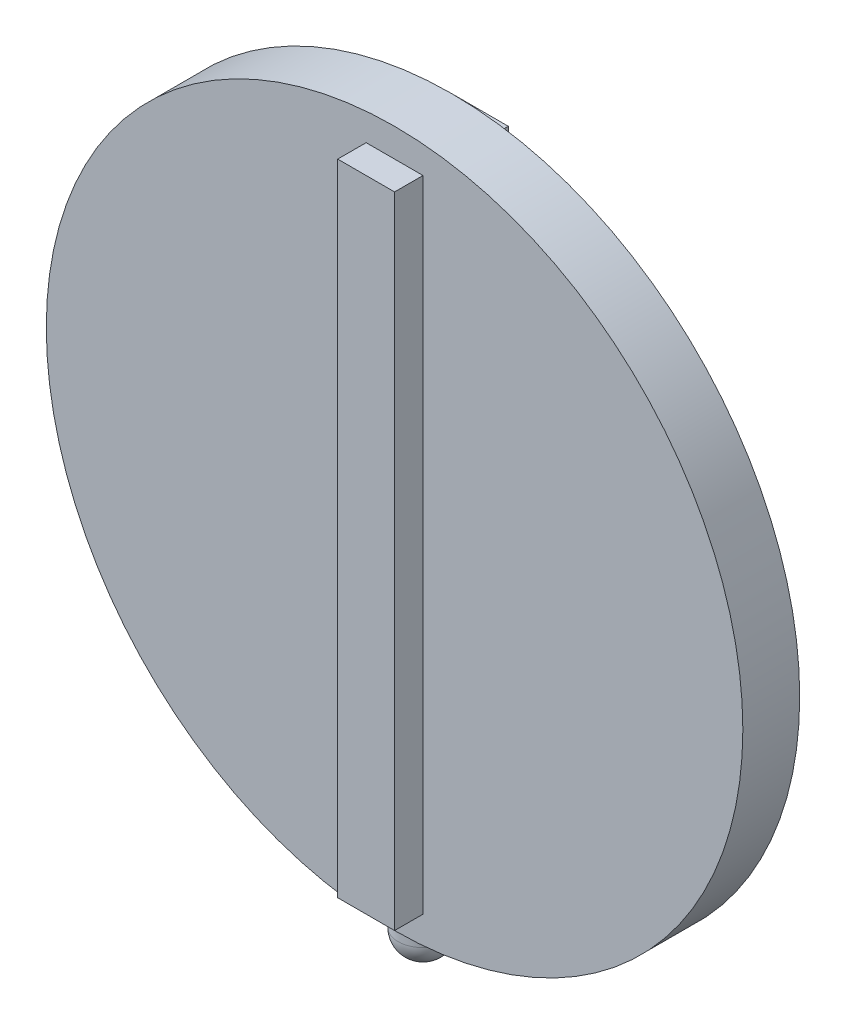
SolidWorks part; units mm, degrees
ref_plane "前视基准面" through (0, 0, 0) normal (0, 0, 1) x (1, 0, 0)
ref_plane "上视基准面" through (0, 0, 0) normal (0, 1, 0) x (1, 0, 0)
ref_plane "右视基准面" through (0, 0, 0) normal (1, 0, 0) x (0, 0, -1)
other "Configuration Table"
sketch "草图1" plane through (0, 0, 0) normal (0, 0, 1) x (1, 0, 0)
  circle A0 centre (0, 0) radius 24.5
  dimension "D1" = 49
extrude "凸台-拉伸1" add sketch "草图1" along normal blind 4
sketch "草图2" plane through (0, 0, 4) normal (0, 0, 1) x (1, 0, 0)
  line L1 (-2, 22.5) -> (2, 22.5)
  line L2 (-2, 22.5) -> (-2, -22.5)
  line L3 (-2, -22.5) -> (2, -22.5)
  line L4 (2, 22.5) -> (2, -22.5)
  line L5 (-2, 22.5) -> (2, -22.5) construction
  line L6 (-2, -22.5) -> (2, 22.5) construction
  point P0 (0, 0)
  dimension "D1" = 45
  dimension "D2" = 4
extrude "凸台-拉伸2" add sketch "草图2" along normal blind 2 contours L2 L1 L4 L3
ref_plane "基准面1" through (0, 0, 2) normal (0, 0, 1) x (1, 0, 0)
mirror "镜向1" about plane through (0, 0, 2) normal (0, 0, 1) of "凸台-拉伸2"
ref_plane "基准面2" through (0, -24, 0) normal (0, -1, 0) x (-1, 0, 0)
sketch "草图3" plane through (0, -24, 0) normal (0, -1, 0) x (-1, 0, 0)
  line L0 (-26.95, -2) -> (26.95, -2) construction
  circle A0 centre (0, -2) radius 1.75
  dimension "D1" = 3.5
extrude "凸台-拉伸3" add sketch "草图3" along normal blind 3
fillet "圆角2" radius 1.7 1 edges at (0, -27, 0.25)
